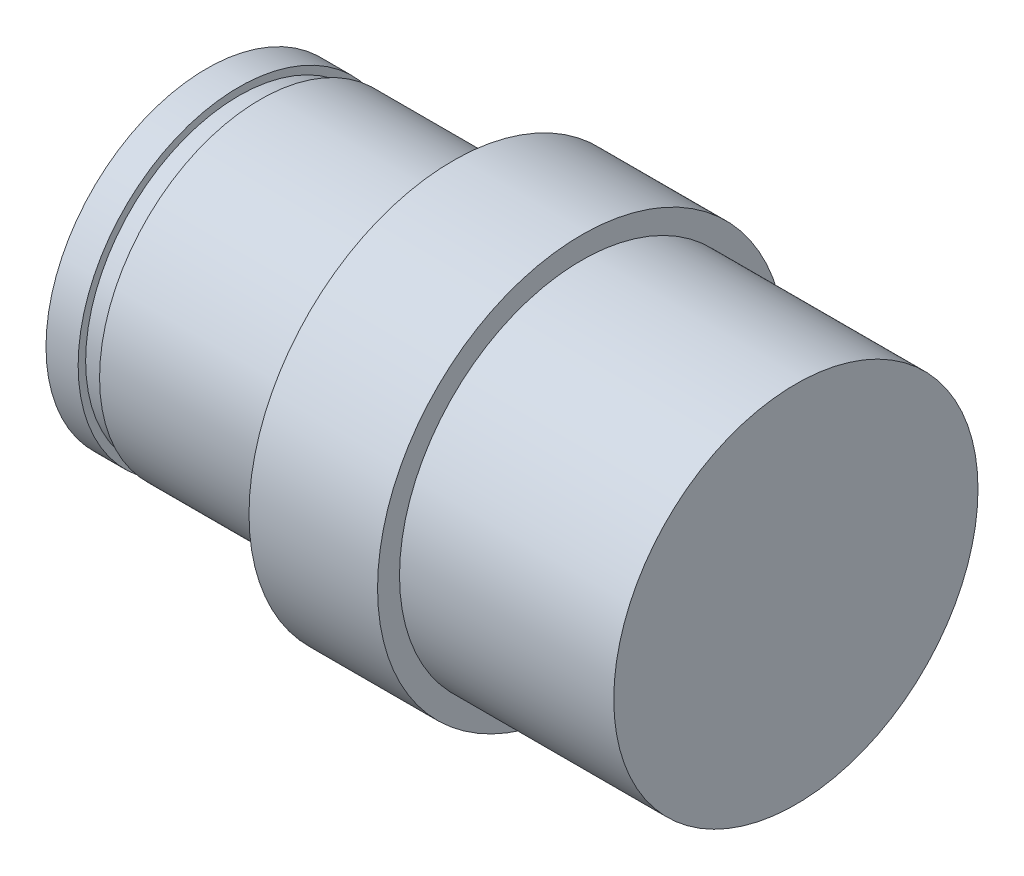
SolidWorks part; units mm, degrees
material "AISI 1020"
ref_plane "Plano frontal" through (0, 0, 0) normal (0, 0, 1) x (1, 0, 0)
ref_plane "Plano superior" through (0, 0, 0) normal (0, 1, 0) x (1, 0, 0)
ref_plane "Plano direito" through (0, 0, 0) normal (1, 0, 0) x (0, 0, -1)
sketch "Esboço1" plane through (0, 0, 0) normal (0, 0, 1) x (1, 0, 0)
  line L0 (0, 0) -> (82.3801, 0) construction
  line L1 (0, 0) -> (0, 7.5)
  line L2 (0, 7.5) -> (11.5, 7.5)
  line L3 (11.5, 7.5) -> (11.5, 9.525)
  line L4 (11.5, 9.525) -> (17.5, 9.525)
  line L5 (17.5, 9.525) -> (17.5, 8.5)
  line L6 (0, 0) -> (27.5, 0)
  line L7 (17.5, 8.5) -> (27.5, 8.5)
  line L8 (27.5, 8.5) -> (27.5, 0)
  dimension "D1" = 15
  dimension "D2" = 11.5
  dimension "D3" = 19.05
  dimension "D4" = 6
  dimension "D5" = 10
  dimension "D6" = 17
revolve "Revolução1" add sketch "Esboço1" angle 360 about L0
sketch "Esboço2" plane through (0, 0, 0) normal (0, 0, 1) x (1, 0, 0)
  line L0 (11.5, 7.5) -> (0, 7.5) construction
  line L1 (1.5, 7.5) -> (2.5, 7.5)
  line L2 (1.5, 7.5) -> (1.5, 7.15)
  line L3 (1.5, 7.15) -> (2.5, 7.15)
  line L4 (2.5, 7.5) -> (2.5, 7.15)
  line L5 (0, 0) -> (14.7526, 0) construction
  line L6 (0, 7.5) -> (0, -7.5) construction
  dimension "D1" = 1
  dimension "D2" = 14.3
  dimension "D3" = 2.5
revolve "Corte-Revolução1" cut sketch "Esboço2" angle 360 about L5
